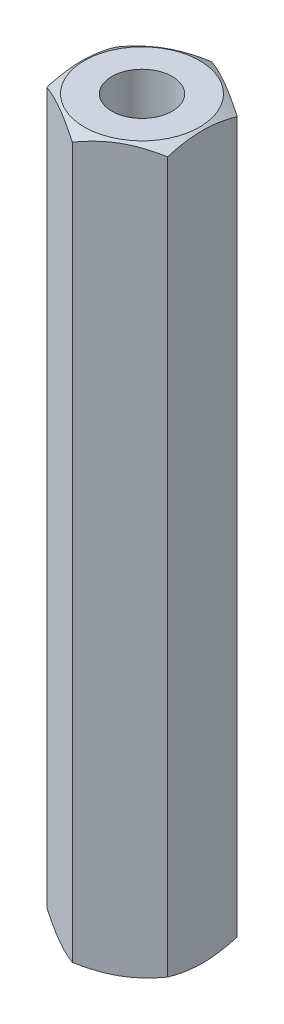
SolidWorks part; units mm, degrees
material "Латунь"
ref_plane "Спереди" through (0, 0, 0) normal (0, 0, 1) x (1, 0, 0)
ref_plane "Сверху" through (0, 0, 0) normal (0, 1, 0) x (1, 0, 0)
ref_plane "Справа" through (0, 0, 0) normal (1, 0, 0) x (0, 0, -1)
sketch "Эскиз1" plane through (0, 0, 0) normal (0, 1, 0) x (1, 0, 0)
  line L1 (0, 2.8868) -> (-2.5, 1.4434)
  line L2 (-2.5, 1.4434) -> (-2.5, -1.4434)
  line L3 (-2.5, -1.4434) -> (0, -2.8868)
  line L4 (0, -2.8868) -> (2.5, -1.4434)
  line L5 (2.5, -1.4434) -> (2.5, 1.4434)
  line L6 (2.5, 1.4434) -> (0, 2.8868)
  circle A0 centre (0, 0) radius 2.5 construction
  dimension "D1" = 5
extrude "Бобышка-Вытянуть1" add sketch "Эскиз1" along normal blind 30
hole_wizard "Отверстие обработанное метчиком M31" positions "Эскиз3" profile "Эскиз2" tap size "M3" standard "Din" end condition through all
sketch "Эскиз3" plane through (0, 30, 0) normal (0, 1, 0) x (1, 0, 0)
  point P0 (0, 0)
sketch "Эскиз2" plane through (0, 30, 0) normal (1, 0, 0) x (0, 0, 1)
  line L0 (0, 0) -> (0, 30)
  line L1 (0, 30) -> (1.25, 30)
  line L2 (1.25, 30) -> (1.25, 0)
  line L5 (1.25, 0) -> (0, 0)
  line L11 (0, -6.35) -> (0, 107.95) construction
  dimension "Диаметр проходного сверла" = 2.5
  dimension "Глубина проходного сверла" = 30
cosmetic thread "Отверстие резьбы1" parameters "D2"=3
sketch "Эскиз4" plane through (0, 0, 0) normal (1, 0, 0) x (0, 0, -1)
  line L0 (0, 0) -> (0, 30) construction
  line L1 (-1.4434, 30) -> (1.4434, 30) construction
  line L2 (1.8635, 30.3021) -> (3.6398, 29.2765)
  line L3 (1.8635, 30.3021) -> (1.8635, 31.3815)
  line L4 (1.8635, 31.3815) -> (3.6398, 31.3815)
  line L5 (3.6398, 31.3815) -> (3.6398, 29.2765)
  line L7 (1.4434, 30) -> (2.8868, 30) construction
  line L8 (2.8868, 30) -> (2.8868, 0) construction
  line L9 (0, 15) -> (5.2062, 15) construction
  line L10 (1.8635, -0.3021) -> (3.6398, 0.7235)
  line L11 (3.6398, -1.3815) -> (3.6398, 0.7235)
  line L12 (1.8635, -1.3815) -> (3.6398, -1.3815)
  line L13 (1.8635, -0.3021) -> (1.8635, -1.3815)
  point P11 (2.3868, 30)
  dimension "D1" = 60
  dimension "D2" = 0.5
revolve "Вырез-Повернуть1" cut sketch "Эскиз4" angle 360 about L0
